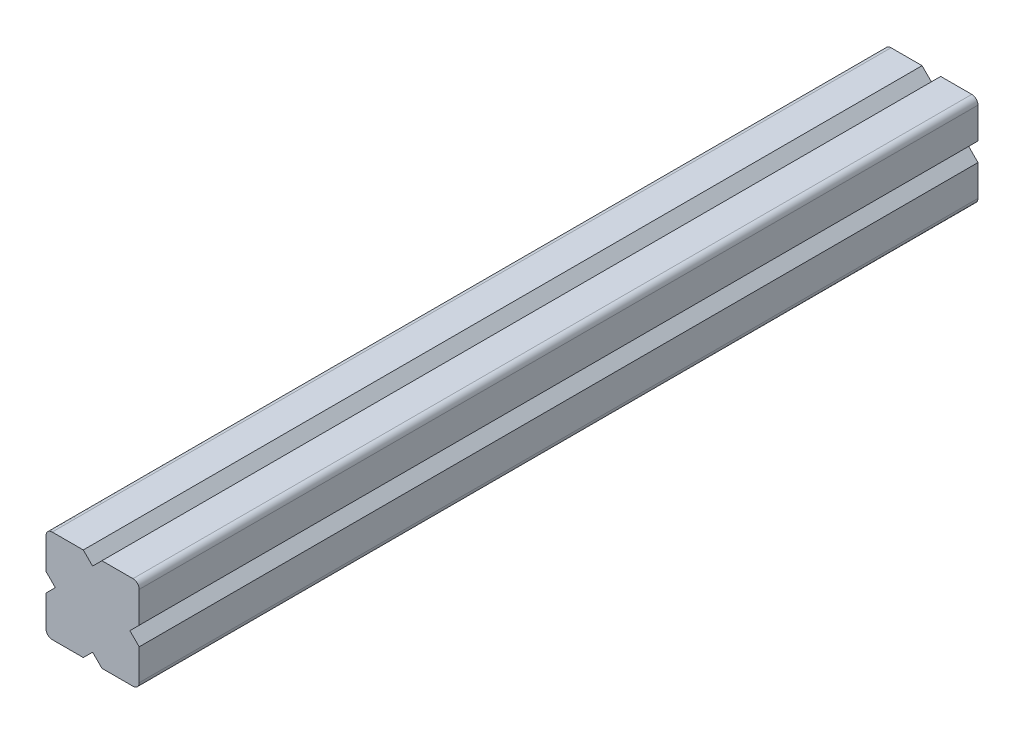
SolidWorks part; units mm, degrees
ref_plane "정면" through (0, 0, 0) normal (0, 0, 1) x (1, 0, 0)
ref_plane "윗면" through (0, 0, 0) normal (0, 1, 0) x (1, 0, 0)
ref_plane "우측면" through (0, 0, 0) normal (1, 0, 0) x (0, 0, -1)
sketch "스케치1" plane through (0, 0, 0) normal (0, 0, 1) x (1, 0, 0)
  line L0 (0, 26.496) -> (0, -26.496) construction
  line L1 (-32.2573, 0) -> (32.2573, 0) construction
  line L4 (-15, 13) -> (-15, 3)
  line L6 (-15, 13) -> (-13, 13) construction
  line L7 (-15, -3) -> (-15, -13)
  line L8 (-15, 3) -> (-12, 0)
  line L9 (-15, 0) -> (-15, -3) construction
  line L10 (-12, 0) -> (-15, -3)
  line L11 (13, 15) -> (3, 15)
  line L13 (3, 15) -> (0, 12)
  line L14 (0, 12) -> (-3, 15)
  line L15 (-3, 15) -> (-13, 15)
  line L16 (15, -13) -> (15, -3)
  line L18 (15, -3) -> (12, 0)
  line L19 (-15, -3) -> (-12, 0)
  line L20 (-12, 0) -> (-15, 3)
  line L21 (12, 0) -> (15, 3)
  line L22 (15, 3) -> (15, 13)
  line L23 (-13, -15) -> (-3, -15)
  line L24 (-3, -15) -> (0, -12)
  line L25 (0, -12) -> (3, -15)
  line L26 (3, -15) -> (13, -15)
  arc A0 (-15, 13) -> (-13, 15) centre (-13, 13) cw
  arc A3 (-15, -13) -> (-13, -15) centre (-13, -13) ccw
  arc A4 (15, -13) -> (13, -15) centre (13, -13) cw
  arc A5 (15, 13) -> (13, 15) centre (13, 13) ccw
  point P5 (0, 0)
  point P6 (0, 0)
  point P44 (0, 0)
  point P47 (0, 0)
  dimension "D4" = 4
  dimension "D1" = 12
  dimension "D2" = 15
  dimension "D3" = 2
  dimension "D5" = 3
  dimension "D6" = 3
  dimension "D7" = 45
extrude "보스-돌출1" add sketch "스케치1" along normal mid plane 270 contours L22 A5 L11 L13 L14 L15 A0 L4 L8 L10 L7 A3 L23 L24 L25 L26 A4 L16 L18 L21
